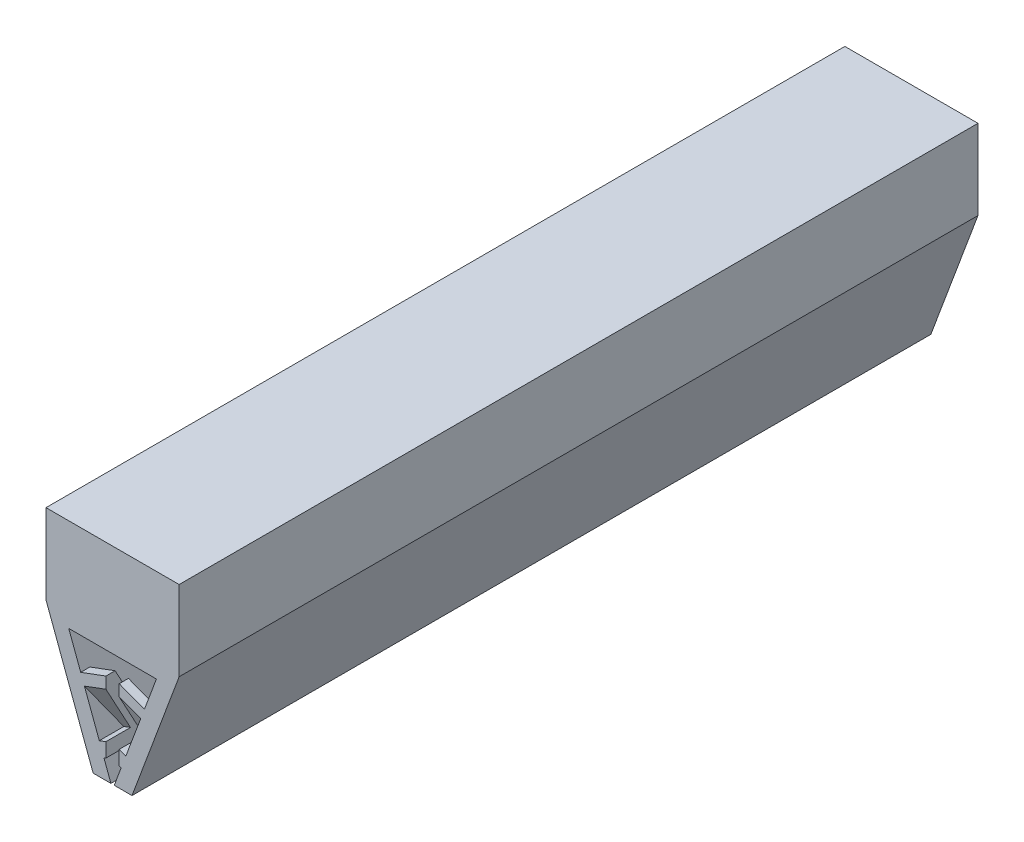
SolidWorks part; units mm, degrees
ref_plane "Alzado" through (0, 0, 0) normal (0, 0, 1) x (1, 0, 0)
ref_plane "Planta" through (0, 0, 0) normal (0, 1, 0) x (1, 0, 0)
ref_plane "Vista lateral" through (0, 0, 0) normal (1, 0, 0) x (0, 0, -1)
sketch "Croquis1" plane through (0, 0, 0) normal (0, 0, 1) x (1, 0, 0)
  line L0 (0, 0) -> (-6.5865, 0)
  line L1 (-6.5865, 0) -> (-0.25, -17)
  line L2 (-0.25, -17) -> (-0.25, -20)
  line L3 (-0.25, -20) -> (-2.918, -20)
  line L4 (-2.918, -20) -> (-2.918, -17)
  line L5 (-2.918, -17) -> (-10, 2)
  line L6 (-10, 2) -> (-10, 14)
  line L7 (-10, 14) -> (0, 14)
  line L8 (0, 14) -> (0, 0)
  line L9 (-0.25, -17) -> (-2.918, -17)
  line L10 (0, 14) -> (0, -24.8871) construction
  point P8 (-6.9087, 0)
  point P11 (0, 0)
  dimension "D1" = 2.5
  dimension "D2" = 3
  dimension "D3" = 10
  dimension "D4" = 20
  dimension "D5" = 0.5
  dimension "D6" = 12
  dimension "D7" = 14
extrude "Saliente-Extruir1" add sketch "Croquis1" along normal mid plane 120 contours L9 L1 L0 L8 L7 L6 L5
sketch "Croquis2" plane through (-5.7831, -2.1556, 0) normal (0.937, 0.3493, 0) x (0, 0, -1)
  line L0 (0, 23.6033) -> (0, -25.0631) construction
  line L1 (-60, 2.3004) -> (-60, -15.8421) construction
  line L2 (60, -12.8421) -> (-60, -12.8421)
  line L3 (0, -12.8421) -> (0, -10.8421)
  line L4 (60, -10.8421) -> (-60, -10.8421)
  line L5 (-60, -12.8421) -> (-60, -10.8421)
  line L6 (-60, -15.8421) -> (60, -15.8421) construction
  line L7 (-4, -10.8421) -> (-8.6188, -2.8421)
  line L8 (-8.6188, -2.8421) -> (-10.9282, -2.8421)
  line L9 (-10.9282, -2.8421) -> (-6.3094, -10.8421)
  line L10 (-6.3094, -10.8421) -> (-4, -10.8421)
  line L11 (-16.3094, -10.8421) -> (-14, -10.8421)
  line L12 (-14, -10.8421) -> (-18.6188, -2.8421)
  line L13 (-18.6188, -2.8421) -> (-20.9282, -2.8421)
  line L14 (-20.9282, -2.8421) -> (-16.3094, -10.8421)
  line L15 (-26.3094, -10.8421) -> (-24, -10.8421)
  line L16 (-24, -10.8421) -> (-28.6188, -2.8421)
  line L17 (-28.6188, -2.8421) -> (-30.9282, -2.8421)
  line L18 (-30.9282, -2.8421) -> (-26.3094, -10.8421)
  line L19 (-36.3094, -10.8421) -> (-34, -10.8421)
  line L20 (-34, -10.8421) -> (-38.6188, -2.8421)
  line L21 (-38.6188, -2.8421) -> (-40.9282, -2.8421)
  line L22 (-40.9282, -2.8421) -> (-36.3094, -10.8421)
  line L23 (-46.3094, -10.8421) -> (-44, -10.8421)
  line L24 (-44, -10.8421) -> (-48.6188, -2.8421)
  line L25 (-48.6188, -2.8421) -> (-50.9282, -2.8421)
  line L26 (-50.9282, -2.8421) -> (-46.3094, -10.8421)
  line L27 (-56.3094, -10.8421) -> (-54, -10.8421)
  line L28 (-54, -10.8421) -> (-58.6188, -2.8421)
  line L29 (-58.6188, -2.8421) -> (-60.9282, -2.8421)
  line L30 (-60.9282, -2.8421) -> (-56.3094, -10.8421)
  line L31 (-6.3094, -10.8421) -> (-16.3094, -10.8421) construction
  line L32 (60, -12.8421) -> (60, -10.8421)
  line L33 (60.9282, -2.8421) -> (56.3094, -10.8421)
  line L34 (58.6188, -2.8421) -> (60.9282, -2.8421)
  line L35 (54, -10.8421) -> (58.6188, -2.8421)
  line L36 (56.3094, -10.8421) -> (54, -10.8421)
  line L37 (50.9282, -2.8421) -> (46.3094, -10.8421)
  line L38 (48.6188, -2.8421) -> (50.9282, -2.8421)
  line L39 (44, -10.8421) -> (48.6188, -2.8421)
  line L40 (46.3094, -10.8421) -> (44, -10.8421)
  line L41 (40.9282, -2.8421) -> (36.3094, -10.8421)
  line L42 (38.6188, -2.8421) -> (40.9282, -2.8421)
  line L43 (34, -10.8421) -> (38.6188, -2.8421)
  line L44 (36.3094, -10.8421) -> (34, -10.8421)
  line L45 (30.9282, -2.8421) -> (26.3094, -10.8421)
  line L46 (28.6188, -2.8421) -> (30.9282, -2.8421)
  line L47 (24, -10.8421) -> (28.6188, -2.8421)
  line L48 (26.3094, -10.8421) -> (24, -10.8421)
  line L49 (20.9282, -2.8421) -> (16.3094, -10.8421)
  line L50 (18.6188, -2.8421) -> (20.9282, -2.8421)
  line L51 (14, -10.8421) -> (18.6188, -2.8421)
  line L52 (16.3094, -10.8421) -> (14, -10.8421)
  line L53 (10.9282, -2.8421) -> (6.3094, -10.8421)
  line L54 (8.6188, -2.8421) -> (10.9282, -2.8421)
  line L55 (4, -10.8421) -> (8.6188, -2.8421)
  line L56 (6.3094, -10.8421) -> (4, -10.8421)
  line M30 (60, -15.8421) -> (60, 2.3004)
  line M32 (-60, 2.3004) -> (-60, -15.8421)
  dimension "D1" = 3
  dimension "D2" = 2
  dimension "D3" = 60
  dimension "D4" = 2
  dimension "D5" = 4
  dimension "D6" = 8
  dimension "D8" = 10
  dimension "D7" = 6
extrude "Saliente-Extruir2" add sketch "Croquis2" along normal offset from surface (0.3178 mm away) 1 contours L3 L4 L2 M32 | L30 L4 L28 L29 M32 | L17 L18 L4 L16 | L13 L14 L4 L12 | L47 L4 L45 L46 | L43 L4 L41 L42 | L39 L4 L37 L38 | L35 L4 L33 L34 M30 | L4 L3 L2 M30 | L24 L25 L26 L23 | L20 L21 L22 L19 | L9 L10 L7 L8 | L55 L54 L53 L56 | L51 L50 L49 L52 up to plane "Vista lateral"
mirror "Simetría1" about plane through (0, 0, 0) normal (1, 0, 0) of "Saliente-Extruir1", "Saliente-Extruir2"
